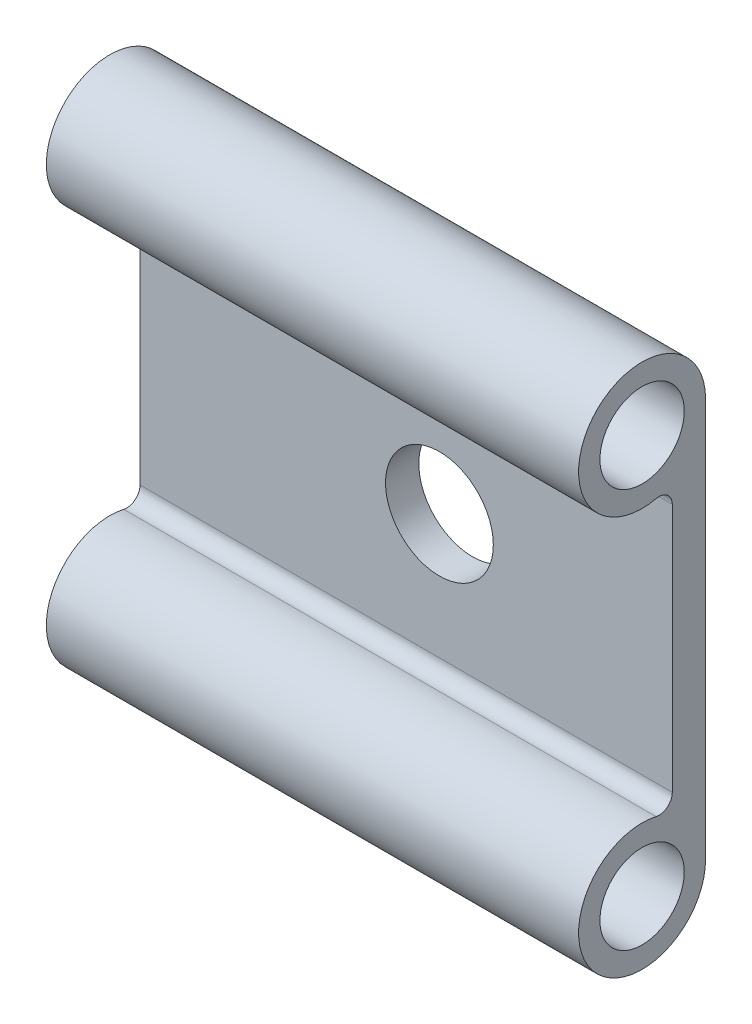
SolidWorks part; units mm, degrees
material "ABS"
ref_plane "Front Plane" through (0, 0, 0) normal (0, 0, 1) x (1, 0, 0)
ref_plane "Top Plane" through (0, 0, 0) normal (0, 1, 0) x (1, 0, 0)
ref_plane "Right Plane" through (0, 0, 0) normal (1, 0, 0) x (0, 0, -1)
sketch "Sketch1" plane through (0, 0, 0) normal (1, 0, 0) x (0, 0, -1)
  line L6 (2.8829, 30.9518) -> (2.8829, 7.1482)
  line L7 (6.0579, 38.1) -> (6.0579, 0)
  circle A3 centre (0, 0) radius 4.0259
  circle A6 centre (0, 38.1) radius 4.0259
  arc A8 (2.8829, 7.1482) -> (1.3334, 5.9093) centre (1.6129, 7.1482) cw
  arc A9 (1.3334, 5.9093) -> (6.0579, 0) centre (0, 0) ccw
  arc A10 (2.8829, 30.9518) -> (1.3334, 32.1907) centre (1.6129, 30.9518) ccw
  arc A11 (1.3334, 32.1907) -> (6.0579, 38.1) centre (0, 38.1) cw
  dimension "D1" = 2.032
  dimension "D4" = 38.1
  dimension "D6" = 8.0518
  dimension "D3" = 3.175
  dimension "D5" = 1.27
extrude "Boss-Extrude1" add sketch "Sketch1" along normal blind 50.8
sketch "Sketch7" plane through (0, 0, -2.8829) normal (0, 0, 1) x (1, 0, 0)
  line L0 (0, 30.9518) -> (0, 7.1482) construction
  line L2 (50.8, 38.1) -> (0, 38.1) construction
  circle A0 centre (28.575, 19.05) radius 5.1435
  dimension "D1" = 28.575
  dimension "D3" = 10.287
  dimension "D2" = 19.05
extrude "Cut-Extrude3" cut sketch "Sketch7" along direction (0, 0, -1) on the side against the normal through all contours A0
sketch "Sketch8" plane through (50.8, 0, 0) normal (1, 0, 0) x (0, 0, -1)
  circle A0 centre (0, 38.1) radius 7.3279
  circle A1 centre (0, 38.1) radius 4.0259 construction
  circle A2 centre (0, 0) radius 7.3279
  arc A3 (6.0579, 38.1) -> (1.3334, 32.1907) centre (0, 38.1) ccw construction
  circle A4 centre (0, 38.1) radius 4.0259
  circle A5 centre (0, 0) radius 4.0259
  dimension "D1" = 1.27
extrude "Boss-Extrude2" [suppressed] add sketch "Sketch8" against normal up to surface (50.8 mm away)
sketch "Sketch9" plane through (50.8, 0, 0) normal (1, 0, 0) x (0, 0, -1)
  circle A1 centre (0, 0) radius 4.0132
  circle A3 centre (0, 38.1) radius 4.0132
  dimension "D1" = 8.0264
extrude "Cut-Extrude4" [suppressed] cut sketch "Sketch9" against normal up to next
fillet "Fillet1" [suppressed] radius 2.54
